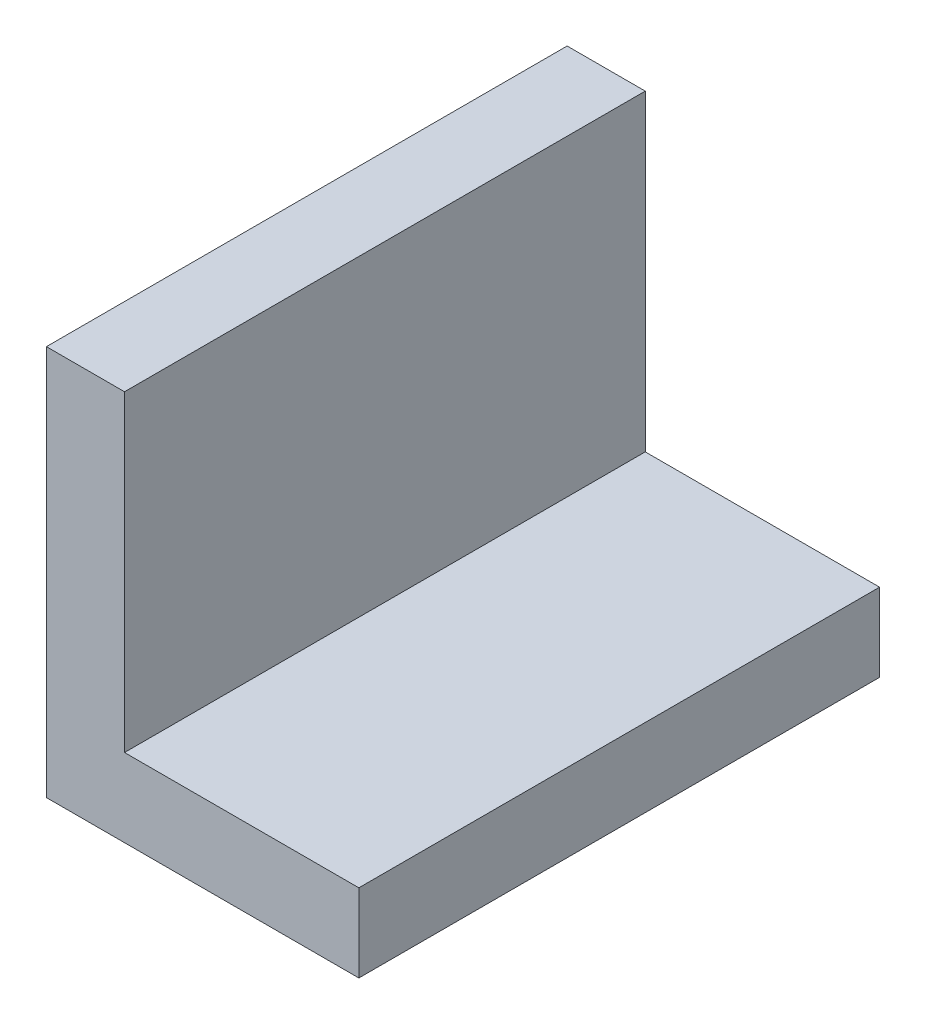
SolidWorks part; units mm, degrees
ref_plane "Front Plane" through (0, 0, 0) normal (0, 0, 1) x (1, 0, 0)
ref_plane "Top Plane" through (0, 0, 0) normal (0, 1, 0) x (1, 0, 0)
ref_plane "Right Plane" through (0, 0, 0) normal (1, 0, 0) x (0, 0, -1)
sketch "Sketch1" plane through (0, 0, 0) normal (0, 0, 1) x (1, 0, 0)
  line L0 (0, 0) -> (0, 75)
  line L1 (0, 75) -> (15, 75)
  line L2 (15, 75) -> (15, 15)
  line L3 (15, 15) -> (60, 15)
  line L4 (60, 15) -> (60, 0)
  line L5 (60, 0) -> (0, 0)
  dimension "D1" = 75
  dimension "D2" = 15
  dimension "D3" = 15
  dimension "D4" = 60
extrude "Boss-Extrude1" add sketch "Sketch1" along normal blind 100
